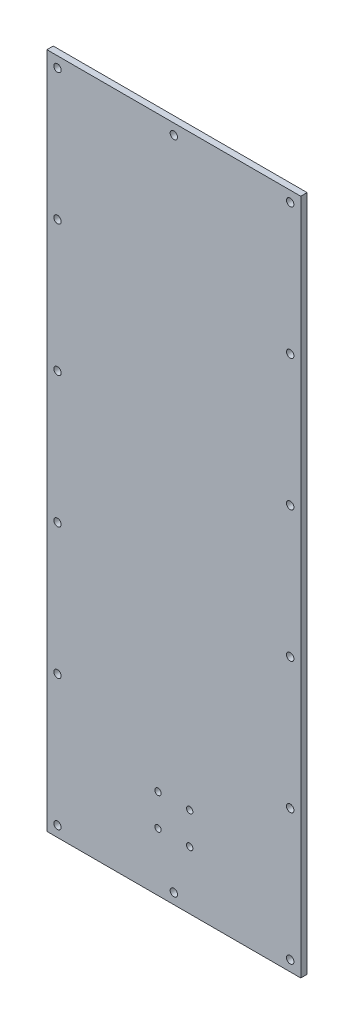
SolidWorks part; units mm, degrees
ref_plane "Plan de face" through (0, 0, 0) normal (0, 0, 1) x (1, 0, 0)
ref_plane "Plan de dessus" through (0, 0, 0) normal (0, 1, 0) x (1, 0, 0)
ref_plane "Plan de droite" through (0, 0, 0) normal (1, 0, 0) x (0, 0, -1)
sketch "Esquisse1" plane through (0, 0, 0) normal (0, 0, 1) x (1, 0, 0)
  line L1 (60, -160) -> (-60, -160)
  line L2 (60, -160) -> (60, 160)
  line L3 (60, 160) -> (-60, 160)
  line L4 (-60, -160) -> (-60, 160)
  line L5 (60, -160) -> (-60, 160) construction
  line L6 (60, 160) -> (-60, -160) construction
  point P0 (0, 0)
  dimension "D1" = 320
  dimension "D2" = 120
extrude "Boss.-Extru.1" add sketch "Esquisse1" along normal blind 3
sketch "Esquisse2" plane through (0, 0, 3) normal (0, 0, 1) x (1, 0, 0)
  line L0 (60, 160) -> (-60, 160) construction
  line L1 (-60, 160) -> (-60, -160) construction
  line L2 (-55, 155) -> (60, 155) construction
  line L3 (60, -160) -> (60, 160) construction
  line L4 (-55, 155) -> (-55, -160) construction
  line L5 (-60, -160) -> (60, -160) construction
  line L6 (-7.5, -117.5) -> (7.5, -117.5) construction
  line L7 (0, 0) -> (0, -160) construction
  line L8 (7.5, -137.5) -> (-7.5, -137.5) construction
  line L9 (12.5, -132.5) -> (12.5, -117.5) construction
  line L10 (7.5, -112.5) -> (-7.5, -112.5) construction
  line L11 (-12.5, -132.5) -> (-12.5, -117.5) construction
  line L12 (12.5, -137.5) -> (-12.5, -112.5) construction
  line L13 (12.5, -112.5) -> (-12.5, -137.5) construction
  line L14 (-7.5, -117.5) -> (-7.5, -132.5) construction
  circle A0 centre (-55, 155) radius 1.7476
  circle A1 centre (0, 155) radius 1.7476
  circle A2 centre (55, 155) radius 1.7476
  circle A3 centre (-55, 93) radius 1.7476
  circle A4 centre (-55, 31) radius 1.7476
  circle A5 centre (-55, -31) radius 1.7476
  circle A6 centre (-55, -93) radius 1.7476
  circle A7 centre (-55, -155) radius 1.7476
  circle A8 centre (0, -155) radius 1.7476
  circle A9 centre (55, -155) radius 1.7476
  circle A11 centre (55, 93) radius 1.7476
  circle A12 centre (55, 31) radius 1.7476
  circle A13 centre (55, -31) radius 1.7476
  circle A14 centre (55, -93) radius 1.7476
  circle A15 centre (0, -125) radius 4.5 construction
  arc A16 (7.5, -137.5) -> (12.5, -132.5) centre (7.5, -132.5) ccw construction
  arc A17 (-7.5, -137.5) -> (-12.5, -132.5) centre (-7.5, -132.5) cw construction
  arc A18 (12.5, -117.5) -> (7.5, -112.5) centre (7.5, -117.5) ccw construction
  arc A19 (-7.5, -112.5) -> (-12.5, -117.5) centre (-7.5, -117.5) ccw construction
  circle A20 centre (-7.5, -117.5) radius 1.5
  circle A21 centre (7.5, -117.5) radius 1.5
  circle A22 centre (7.5, -132.5) radius 1.5
  circle A23 centre (-7.5, -132.5) radius 1.5
  point P61 (25, -125)
  point P62 (0, -125)
  dimension "D8" = 9
  dimension "D10" = 5
  dimension "D12" = 3
  dimension "D1" = 5
  dimension "D2" = 5
  dimension "D4" = 5
  dimension "D6" = 5
  dimension "D9" = 35
  dimension "D11" = 25
  dimension "D3" = 3
  dimension "D5" = 6
  dimension "D13" = 2
  dimension "D14" = 2
extrude "Enlèv. mat.-Extru.1" cut sketch "Esquisse2" against normal blind 10
